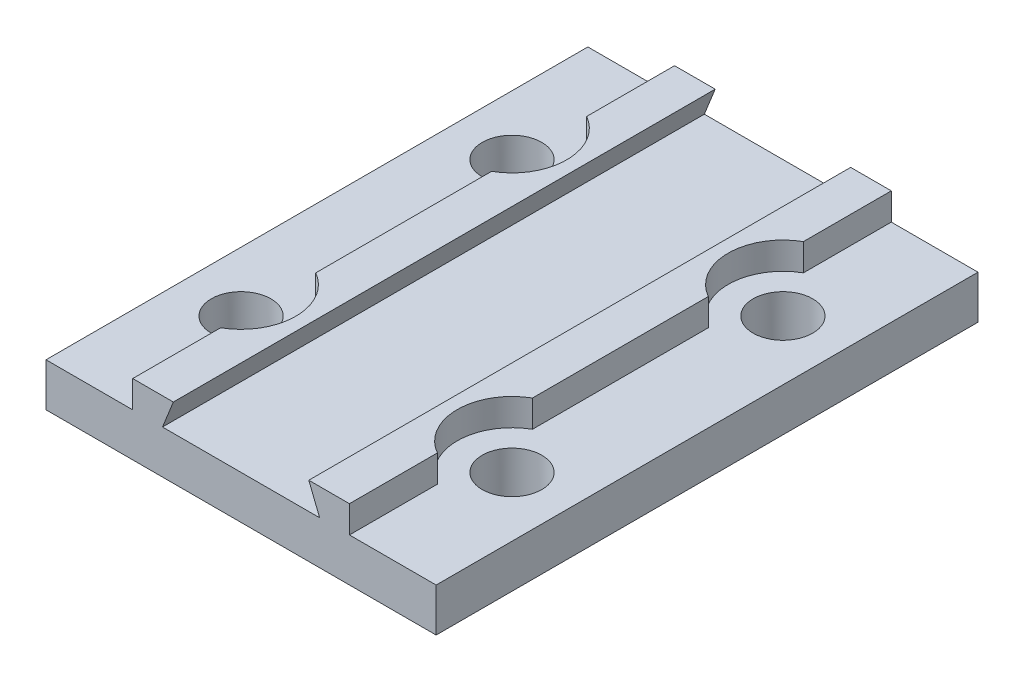
SolidWorks part; units mm, degrees
ref_plane "Front Plane" through (0, 0, 0) normal (0, 0, 1) x (1, 0, 0)
ref_plane "Top Plane" through (0, 0, 0) normal (0, 1, 0) x (1, 0, 0)
ref_plane "Right Plane" through (0, 0, 0) normal (1, 0, 0) x (0, 0, -1)
sketch "Sketch1" plane through (0, 0, 0) normal (0, 1, 0) x (1, 0, 0)
  line L1 (-10, -25) -> (10, -25)
  line L2 (-10, -25) -> (-10, 25)
  line L3 (-10, 25) -> (10, 25)
  line L4 (10, -25) -> (10, 25)
  line L5 (-10, -25) -> (10, 25) construction
  line L6 (-10, 25) -> (10, -25) construction
  point P0 (0, 0)
extrude "Boss-Extrude1" add sketch "Sketch1" along normal blind 12
sketch "Sketch2" plane through (0, 0, 25) normal (0, 0, 1) x (1, 0, 0)
  line L0 (0, 12) -> (0, 9.5) construction
  line L8 (-10, 12) -> (10, 12) construction
  line L9 (0, 9.5) -> (7.25, 9.5)
  line L10 (0, 9.5) -> (-7.25, 9.5)
  line L11 (0, 12) -> (6.25, 12)
  line L12 (0, 12) -> (-6.25, 12)
  line L13 (-7.25, 9.5) -> (-6.25, 12)
  line L14 (6.25, 12) -> (7.25, 9.5)
extrude "Cut-Extrude1" cut sketch "Sketch2" against normal up to next
sketch "Sketch4" plane through (-10, 0, 0) normal (-1, 0, 0) x (0, 0, 1)
  line L1 (-25, 9.5) -> (25, 9.5)
  line L2 (-25, 9.5) -> (-25, 0)
  line L3 (-25, 0) -> (25, 0)
  line L4 (25, 9.5) -> (25, 0)
extrude "Boss-Extrude2" add sketch "Sketch4" along normal blind 8
sketch "Sketch5" plane through (10, 0, 0) normal (1, 0, 0) x (0, 0, -1)
  line L1 (25, 9.5) -> (-25, 9.5)
  line L2 (25, 9.5) -> (25, 0)
  line L3 (25, 0) -> (-25, 0)
  line L4 (-25, 9.5) -> (-25, 0)
extrude "Boss-Extrude3" add sketch "Sketch5" along normal blind 8
sketch "Sketch10" plane through (0, 9.5, 0) normal (0, 1, 0) x (1, 0, 0)
  line L0 (0, -25) -> (12.5, -25) construction
  line L1 (-7.25, -25) -> (7.25, -25) construction
  line L2 (18, -25) -> (10, -25) construction
  line L3 (12.5, -25) -> (12.5, -12.5) construction
  line L4 (12.5, -12.5) -> (-12.5, -12.5) construction
  line L5 (12.5, -12.5) -> (12.5, 12.5) construction
  line L6 (12.5, 12.5) -> (-12.5, 12.5) construction
  circle A0 centre (-12.5, 12.5) radius 2.75
  circle A1 centre (12.5, 12.5) radius 2.75
  circle A2 centre (-12.5, -12.5) radius 2.75
  circle A3 centre (12.5, -12.5) radius 2.75
extrude "Cut-Extrude4" cut sketch "Sketch10" against normal through all and the other way through all
sketch "Sketch13" plane through (0, 0, 0) normal (0, -1, 0) x (1, 0, 0)
  line L1 (-18, -25) -> (18, -25)
  line L2 (-18, -25) -> (-18, 25)
  line L3 (-18, 25) -> (18, 25)
  line L4 (18, -25) -> (18, 25)
  line L5 (-18, -25) -> (18, 25) construction
  line L6 (-18, 25) -> (18, -25) construction
  point P0 (0, 0)
extrude "Cut-Extrude6" cut sketch "Sketch13" against normal blind 5.5
sketch "Sketch14" plane through (0, 9.5, 0) normal (0, 1, 0) x (1, 0, 0)
  circle A0 centre (-12.5, 12.5) radius 5.05
  circle A1 centre (12.5, 12.5) radius 5.05
  circle A2 centre (-12.5, -12.5) radius 5.05
  circle A3 centre (12.5, -12.5) radius 5.05
extrude "Cut-Extrude7" cut sketch "Sketch14" along normal up to next
